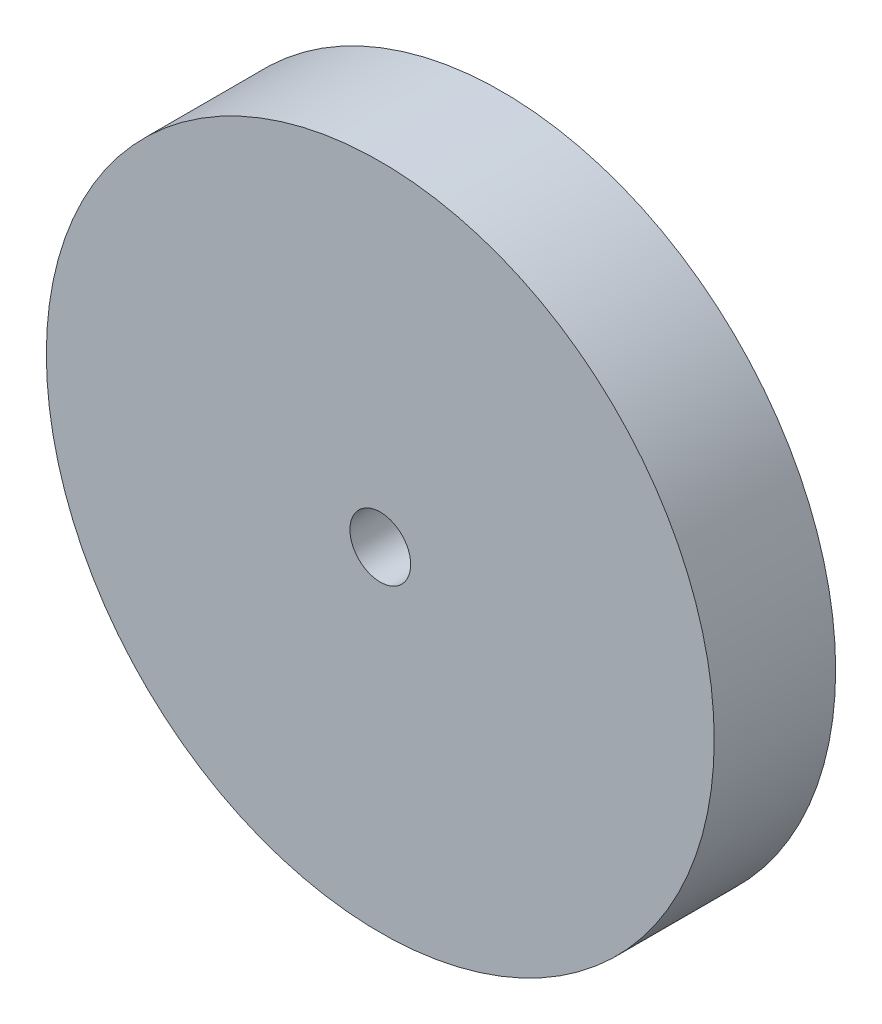
SolidWorks part; units mm, degrees
ref_plane "Front Plane" through (0, 0, 0) normal (0, 0, 1) x (1, 0, 0)
ref_plane "Top Plane" through (0, 0, 0) normal (0, 1, 0) x (1, 0, 0)
ref_plane "Right Plane" through (0, 0, 0) normal (1, 0, 0) x (0, 0, -1)
sketch "Sketch1" plane through (0, 0, 0) normal (0, 0, 1) x (1, 0, 0)
  circle A0 centre (0, 0) radius 27.5
  circle A1 centre (0, 0) radius 2.5
  dimension "D1" = 55
  dimension "D2" = 5
extrude "Boss-Extrude1" add sketch "Sketch1" along normal mid plane 10
